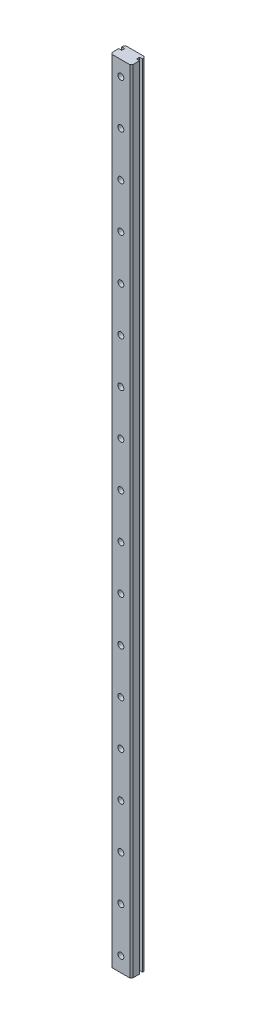
SolidWorks part; units mm, degrees
material "AISI 304"
ref_plane "前视基准面" through (0, 0, 0) normal (0, 0, 1) x (1, 0, 0)
ref_plane "上视基准面" through (0, 0, 0) normal (0, 1, 0) x (1, 0, 0)
ref_plane "右视基准面" through (0, 0, 0) normal (1, 0, 0) x (0, 0, -1)
other "Configuration Table"
sketch "草图1" plane through (0, 0, 0) normal (0, 1, 0) x (1, 0, 0)
  line L0 (0, 0) -> (0, 7.157) construction
  line L1 (-3.5, -2.4) -> (3.5, -2.4)
  line L2 (-3.5, -2.4) -> (-3.5, 2.4)
  line L3 (-3.5, 2.4) -> (3.5, 2.4)
  line L4 (3.5, -2.4) -> (3.5, 2.4)
  line L5 (-3.5, -2.4) -> (3.5, 2.4) construction
  line L6 (-3.5, 2.4) -> (3.5, -2.4) construction
  line L7 (3.5, 1.4) -> (2.5, 1.4)
  line L8 (2.5, 1.4) -> (2.5, 0.4)
  line L9 (2.5, 0.4) -> (3.5, 0.4)
  line L10 (-2.5, 0.4) -> (-3.5, 0.4)
  line L11 (-2.5, 1.4) -> (-2.5, 0.4)
  line L12 (-3.5, 1.4) -> (-2.5, 1.4)
  point P0 (0, 0)
  dimension "D1" = 7
  dimension "D2" = 4.8
  dimension "D3" = 1
  dimension "D4" = 1
  dimension "D5" = 1
extrude "凸台-拉伸1" add sketch "草图1" along normal blind 265 contours L2 L12 L11 L10 L1 L4 L9 L8 L7 L3
sketch "草图2" plane through (0, 0, -2.4) normal (0, 0, -1) x (-1, 0, 0)
  line L0 (3.5, 0) -> (-3.5, 0) construction
  line L1 (-3.5, 265) -> (-3.5, 0) construction
  circle A0 centre (0, 5) radius 1
  circle A1 centre (0, 20) radius 1
  circle A2 centre (0, 35) radius 1
  circle A3 centre (0, 50) radius 1
  circle A4 centre (0, 65) radius 1
  circle A5 centre (0, 80) radius 1
  circle A6 centre (0, 95) radius 1
  circle A7 centre (0, 110) radius 1
  circle A8 centre (0, 125) radius 1
  circle A9 centre (0, 140) radius 1
  circle A10 centre (0, 155) radius 1
  circle A11 centre (0, 170) radius 1
  circle A12 centre (0, 185) radius 1
  circle A13 centre (0, 200) radius 1
  circle A14 centre (0, 215) radius 1
  circle A15 centre (0, 230) radius 1
  circle A16 centre (0, 245) radius 1
  circle A17 centre (0, 260) radius 1
  dimension "D1" = 2
  dimension "D2" = 5
  dimension "D5" = 15
  dimension "D3" = 3.5
  dimension "D4" = 18
extrude "切除-拉伸1" cut sketch "草图2" against normal blind 10
chamfer "倒角1" distance 0.5 angle 45 4 edges at (-3.5, 132.5, 2.4) (3.5, 132.5, 2.4) (-3.5, 132.5, -2.4) (3.5, 132.5, -2.4)
sketch "草图3" plane through (0, 0, -2.4) normal (0, 0, -1) x (-1, 0, 0)
  circle A0 centre (0, 5) radius 2.3833
  circle A1 centre (0, 20) radius 2.3833
  circle A2 centre (0, 35) radius 2.3833
  circle A3 centre (0, 50) radius 2.3833
  circle A4 centre (0, 65) radius 2.3833
  circle A5 centre (0, 80) radius 2.3833
  circle A6 centre (0, 95) radius 2.3833
  circle A7 centre (0, 110) radius 2.3833
  circle A8 centre (0, 125) radius 2.3833
  circle A9 centre (0, 140) radius 2.3833
  circle A10 centre (0, 155) radius 2.3833
  circle A11 centre (0, 170) radius 2.3833
  circle A12 centre (0, 185) radius 2.3833
  circle A13 centre (0, 200) radius 2.3833
  circle A14 centre (0, 215) radius 2.3833
  circle A15 centre (0, 230) radius 2.3833
  circle A16 centre (0, 245) radius 2.3833
  circle A17 centre (0, 260) radius 2.3833
  dimension "D1" = 4.7666
  dimension "D3" = 15
  dimension "D2" = 18
extrude "切除-拉伸2" cut sketch "草图3" against normal blind 1
